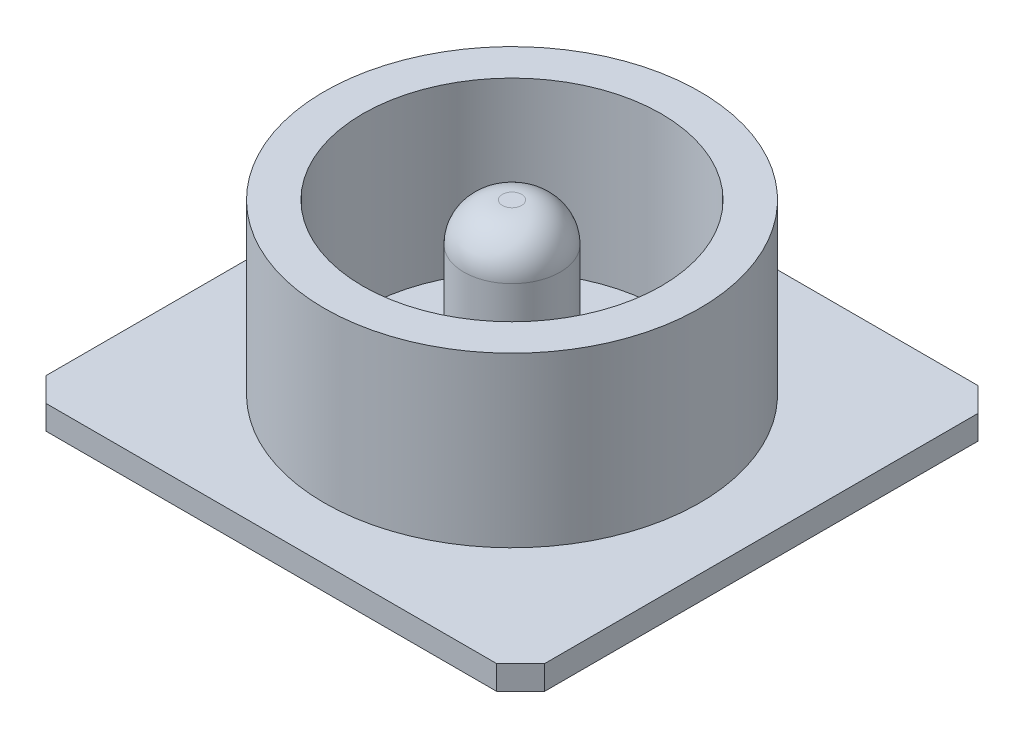
SolidWorks part; units mm, degrees
ref_plane "Front Plane" through (0, 0, 0) normal (0, 0, 1) x (1, 0, 0)
ref_plane "Top Plane" through (0, 0, 0) normal (0, 1, 0) x (1, 0, 0)
ref_plane "Right Plane" through (0, 0, 0) normal (1, 0, 0) x (0, 0, -1)
sketch "Sketch1" plane through (0, 0, 0) normal (0, 1, 0) x (1, 0, 0)
  line L0 (1.3155, -1.27) -> (1.3155, 1.27)
  line L1 (1.3155, 1.27) -> (-1.3155, 1.27)
  line L2 (-1.3155, 1.27) -> (-1.3155, -1.27)
  line L3 (-1.3155, -1.27) -> (1.3155, -1.27)
extrude "Boss-Extrude1" add sketch "Sketch1" against normal blind 0.127
sketch "Sketch2" plane through (0, 0, 0) normal (0, 1, 0) x (-1, 0, 0)
  circle A0 centre (0, 0) radius 0.9906
extrude "Boss-Extrude2" add sketch "Sketch2" along normal blind 0.889
hole_wizard "Hole1" positions "Sketch4" profile "Sketch3" legacy
sketch "Sketch4" plane through (0, 0.889, 0) normal (0, 1, 0) x (-1, 0, 0)
  point P0 (0, 0)
sketch "Sketch3" plane through (0, 0.889, 0) normal (1, 0, 0) x (0, 0, 1)
  line L0 (0, 0) -> (0, 1.016)
  line L1 (0, 1.016) -> (0.7874, 1.016)
  line L2 (0.7874, 1.016) -> (0.7874, 0)
  line L3 (0.7874, 0) -> (0, 0)
  line L4 (0, 110) -> (0, -10) construction
  dimension "Diameter" = 1.5748
  dimension "Depth" = 1.016
sketch "Sketch5" plane through (0, 0, 0) normal (0, 0, 1) x (1, 0, 0)
  line L0 (0.254, 0.889) -> (0, 0.889)
  line L1 (0, 0.889) -> (0, 0)
  line L2 (0, 0) -> (0.254, 0)
  line L3 (0.254, 0) -> (0.254, 0.889)
  line L4 (0, 0.889) -> (0, 0) construction
revolve "Revolve1" add sketch "Sketch5" angle 360 about L4
chamfer "Chamfer1" distance 0.127 angle 45 4 edges at (-1.3155, -0.0635, 1.27) (-1.3155, -0.0635, -1.27) (1.3155, -0.0635, 1.27) (1.3155, -0.0635, -1.27)
fillet "Fillet1" radius 0.2032 1 edges at (0, 0.889, -0.254)
sketch "Sketch6" plane through (0, -0.127, 0) normal (0, -1, 0) x (1, 0, 0)
  circle A0 centre (0, 0) radius 0.7874 construction
  circle A1 centre (0, 0) radius 0.7874
extrude "Boss-Extrude3" add sketch "Sketch6" against normal up to surface (0.127 mm away) up to face at (0, 0, 0)
